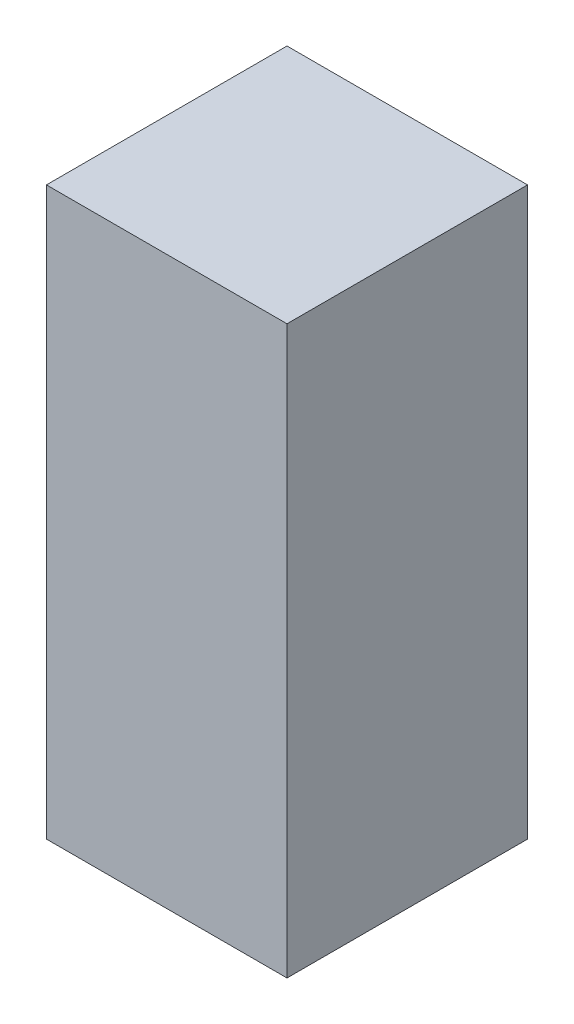
SolidWorks part; units mm, degrees
ref_plane "Plan de face" through (0, 0, 0) normal (0, 0, 1) x (1, 0, 0)
ref_plane "Plan de dessus" through (0, 0, 0) normal (0, 1, 0) x (1, 0, 0)
ref_plane "Plan de droite" through (0, 0, 0) normal (1, 0, 0) x (0, 0, -1)
sketch "Esquisse1" plane through (0, 0, 0) normal (0, 0, 1) x (1, 0, 0)
  line L1 (-9.15, 21.55) -> (9.15, 21.55)
  line L2 (-9.15, 21.55) -> (-9.15, -21.55)
  line L3 (-9.15, -21.55) -> (9.15, -21.55)
  line L4 (9.15, 21.55) -> (9.15, -21.55)
  line L5 (-9.15, 21.55) -> (9.15, -21.55) construction
  line L6 (-9.15, -21.55) -> (9.15, 21.55) construction
  point P0 (0, 0)
  dimension "D1" = 18.3
  dimension "D2" = 43.1
extrude "Boss.-Extru.1" add sketch "Esquisse1" against normal blind 18.3
